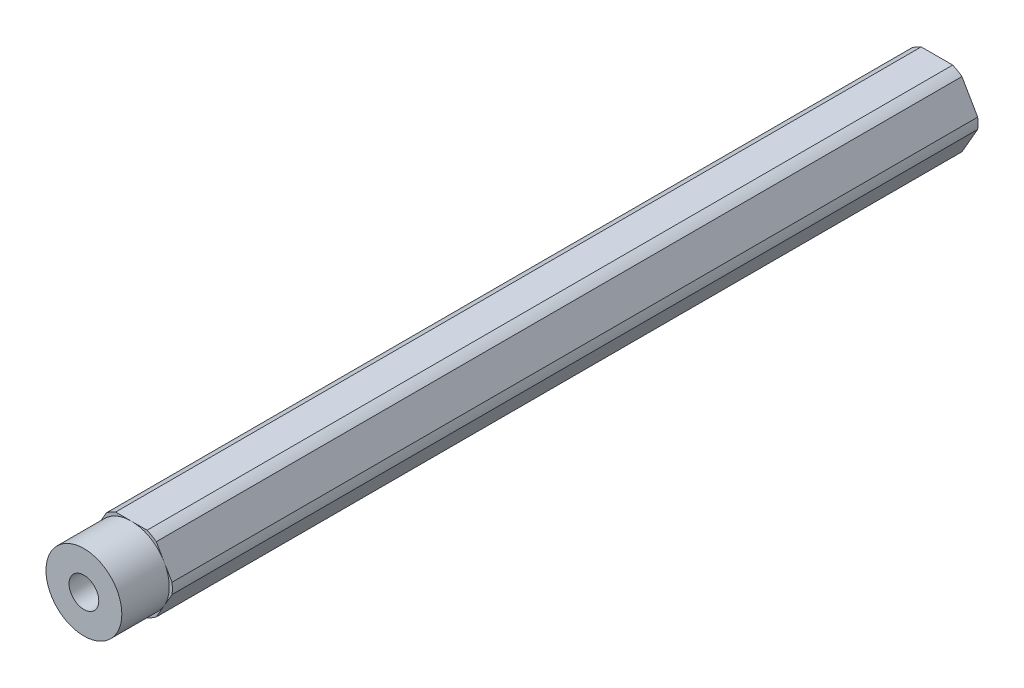
SolidWorks part; units mm, degrees
material "6061-T6 (SS)"
ref_plane "Front Plane" through (0, 0, 0) normal (0, 0, 1) x (1, 0, 0)
ref_plane "Top Plane" through (0, 0, 0) normal (0, 1, 0) x (1, 0, 0)
ref_plane "Right Plane" through (0, 0, 0) normal (1, 0, 0) x (0, 0, -1)
sketch "Sketch1" plane through (0, 0, 0) normal (0, 0, 1) x (1, 0, 0)
  line L1 (3.6662, 6.35) -> (-3.6662, 6.35)
  line L2 (-3.6662, 6.35) -> (-7.3323, 0)
  line L3 (-7.3323, 0) -> (-3.6662, -6.35)
  line L4 (-3.6662, -6.35) -> (3.6662, -6.35)
  line L5 (3.6662, -6.35) -> (7.3323, 0)
  line L6 (7.3323, 0) -> (3.6662, 6.35)
  circle A0 centre (0, 0) radius 6.35 construction
  circle A2 centre (0, 0) radius 6.875
  point P1 (0, 6.35)
  dimension "D2" = 13.75
  dimension "D1" = 12.7
extrude "Boss-Extrude1" add sketch "Sketch1" along normal mid plane 134.8867
sketch "Sketch4" plane through (0, 0, 67.4433) normal (0, 0, 1) x (1, 0, 0)
  circle A0 centre (0, 0) radius 6.35
  circle A2 centre (0, 0) radius 2.4892
  dimension "D1" = 12.7
  dimension "D2" = 4.9784
extrude "Boss-Extrude2" add sketch "Sketch4" along normal blind 7.9375
hole_wizard "#10-32 Tapped Hole1" positions "Sketch5" profile "Sketch6" tap size "#10-32" standard "ANSI Inch" end condition through all
sketch "Sketch5" plane through (0, 0, -67.4433) normal (0, 0, -1) x (-1, 0, 0)
  point P0 (0, 0)
cosmetic thread "Hole Thread1" parameters "D2"=4.826
sketch "Sketch6" plane through (0, 0, -67.4433) normal (1, 0, 0) x (0, 1, 0)
  line L0 (0, 0) -> (0, 142.8242)
  line L1 (0, 142.8242) -> (2.0193, 142.8242)
  line L2 (2.0193, 142.8242) -> (2.0193, 1.0287)
  line L3 (2.0193, 1.0287) -> (3.048, 0)
  line L5 (3.048, 0) -> (0, 0)
  line L6 (-2.0193, 1.0287) -> (-3.048, 0) construction
  line L11 (0, -6.35) -> (0, 107.95) construction
  dimension "Thru Tap Drill Dia." = 4.0386
  dimension "Thru Tap Drill Depth" = 142.8242
  dimension "Near C'Sink Dia." = 6.096
  dimension "Near C'Sink Angle" = 90
equation "\"D2@Sketch1\"=13.75mm"
